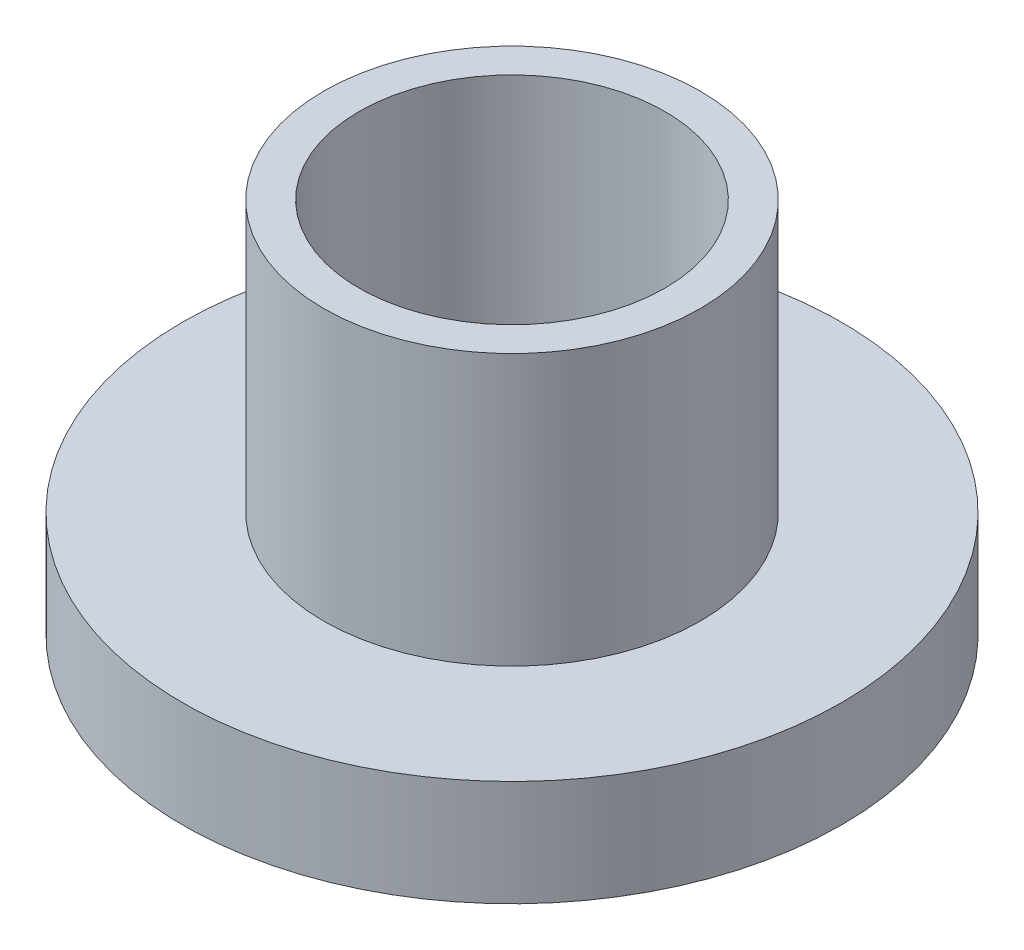
SolidWorks part; units mm, degrees
ref_plane "Front Plane" through (0, 0, 0) normal (0, 0, 1) x (1, 0, 0)
ref_plane "Top Plane" through (0, 0, 0) normal (0, 1, 0) x (1, 0, 0)
ref_plane "Right Plane" through (0, 0, 0) normal (1, 0, 0) x (0, 0, -1)
sketch "Sketch1" plane through (0, 0, 0) normal (0, 0, 1) x (1, 0, 0)
  line L0 (-0.2079, -2.7975) -> (-0.2079, -0.5115)
  line L1 (-4.2719, 5.3305) -> (3.8561, 5.3305)
  line L2 (-4.2719, 5.3305) -> (-4.2719, -2.7975)
  line L3 (-4.2719, -2.7975) -> (3.8561, -2.7975)
  line L4 (3.8561, 5.3305) -> (3.8561, -2.7975)
  line L5 (-7.3199, -0.5115) -> (6.9041, -0.5115)
  line L6 (-7.3199, -0.5115) -> (-7.3199, -2.7975)
  line L7 (-7.3199, -2.7975) -> (6.9041, -2.7975)
  line L8 (6.9041, -0.5115) -> (6.9041, -2.7975)
  line L9 (-3.5099, 5.3305) -> (3.0941, 5.3305)
  line L10 (-3.5099, 5.3305) -> (-3.5099, -2.7975)
  line L11 (-3.5099, -2.7975) -> (3.0941, -2.7975)
  line L12 (3.0941, 5.3305) -> (3.0941, -2.7975)
  point P8 (-0.2079, -2.7975)
  dimension "D1" = 8.128
  dimension "D2" = 14.224
  dimension "D3" = 7.112
  dimension "D4" = 2.286
  dimension "D5" = 8.128
  dimension "D6" = 6.604
  dimension "D7" = 3.302
revolve "Revolve2" add sketch "Sketch1" angle 360 about L0
equation "\"ODFLANGE\"=0.56"
equation "\"D2@Sketch1\"=\"ODFLANGE\""
equation "\"D3@Sketch1\"=\"ODFLANGE\"/2"
equation "\"HFLANGE\"=0.141395"
equation "\"H\"=0.386977"
equation "\"ID\"=0.26"
equation "\"D6@Sketch1\"=\"ID\""
equation "\"D7@Sketch1\"=\"ID\"/2"
